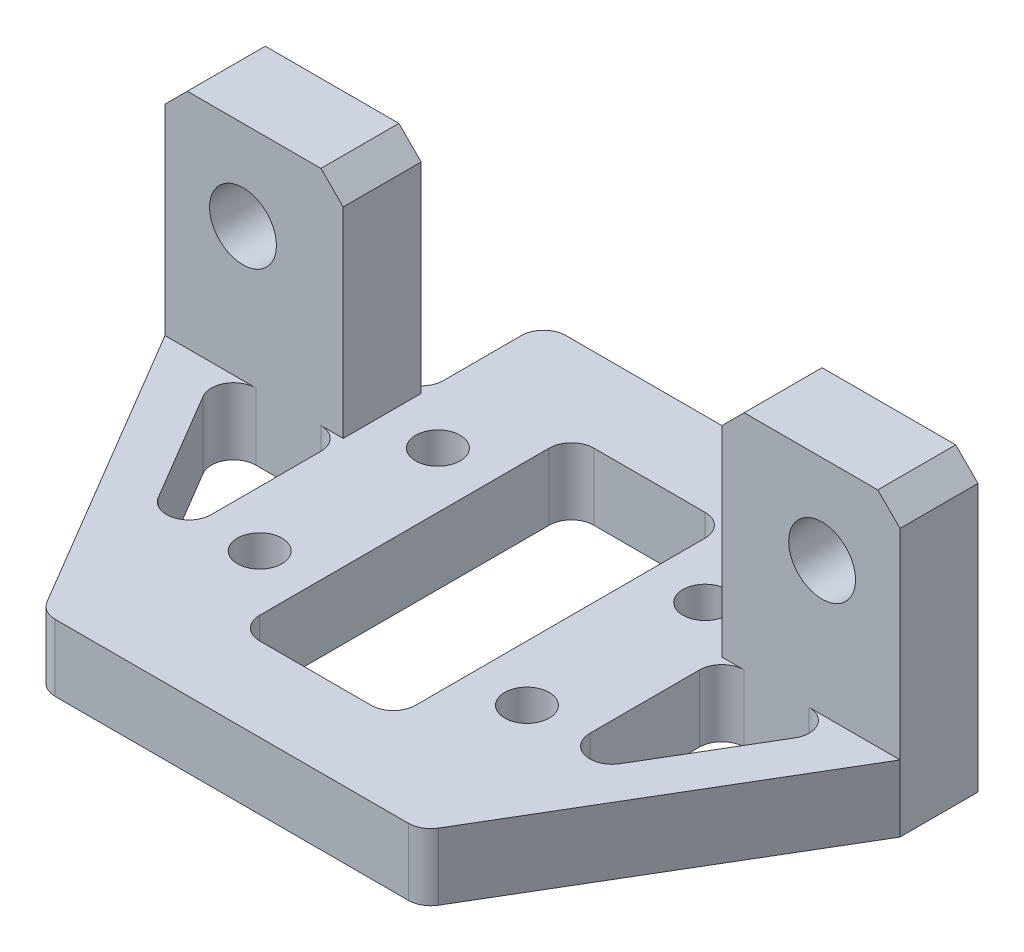
SolidWorks part; units mm, degrees
material "6061-T6 (SS)"
ref_plane "前视基准面" through (0, 0, 0) normal (0, 0, 1) x (1, 0, 0)
ref_plane "上视基准面" through (0, 0, 0) normal (0, 1, 0) x (1, 0, 0)
ref_plane "右视基准面" through (0, 0, 0) normal (1, 0, 0) x (0, 0, -1)
sketch "草图1" plane through (0, 0, 0) normal (0, 1, 0) x (1, 0, 0)
  line L1 (-8.5, 11.25) -> (8.5, 11.25)
  line L2 (-8.5, 11.25) -> (-8.5, -11.25)
  line L3 (-8.5, -11.25) -> (8.5, -11.25)
  line L4 (8.5, 11.25) -> (8.5, -11.25)
  line L5 (-8.5, 11.25) -> (8.5, -11.25) construction
  line L6 (-8.5, -11.25) -> (8.5, 11.25) construction
  point P0 (0, 0)
  dimension "D1" = 17
  dimension "D2" = 22.5
extrude "凸台-拉伸1" add sketch "草图1" along normal blind 3
sketch "草图2" plane through (0, 0, -11.25) normal (0, 0, 1) x (1, 0, 0)
  line L0 (0, 17.6156) -> (0, -12.1631) construction
  line L1 (-16.4166, 0) -> (16.265, 0) construction
  line L3 (-16.5, 13) -> (16.5, 13)
  line L4 (-16.5, 13) -> (-16.5, 0)
  line L5 (-16.5, 0) -> (16.5, 0)
  line L6 (16.5, 13) -> (16.5, 0)
  line L7 (-16.5, 13) -> (16.5, 0) construction
  line L8 (-16.5, 0) -> (16.5, 13) construction
  circle A0 centre (-13, 9) radius 1.5
  circle A1 centre (13, 9) radius 1.5
  point P5 (0, 6.5)
  dimension "D3" = 3
  dimension "D1" = 13
  dimension "D2" = 33
  dimension "D4" = 9
  dimension "D5" = 26
extrude "凸台-拉伸2" add sketch "草图2" along normal blind 3.5 from offset 5.5
sketch "草图3" plane through (0, 0, 0) normal (0, -1, 0) x (1, 0, 0)
  line L0 (0, -28.0972) -> (0, 24.9412) construction
  line L1 (23.039, 0) -> (-25.0172, 0) construction
  circle A0 centre (6, -4) radius 1
  circle A1 centre (-6, -4) radius 1
  circle A2 centre (-6, 4) radius 1
  circle A3 centre (6, 4) radius 1
  dimension "D1" = 2
  dimension "D2" = 12
  dimension "D3" = 8
extrude "切除-拉伸1" cut sketch "草图3" against normal through all
sketch "草图4" plane through (0, 13, 0) normal (0, 1, 0) x (1, 0, 0)
  line L0 (0, 14.4806) -> (0, -10.1377) construction
  line L6 (-6, 4) -> (6, 4) construction
  line L7 (16.5, 2.25) -> (-16.5, 2.25) construction
  line L13 (-8.5, 5.75) -> (8.5, 5.75)
  line L14 (-8.5, 5.75) -> (-8.5, 2.25)
  line L15 (-8.5, 2.25) -> (8.5, 2.25)
  line L16 (8.5, 5.75) -> (8.5, 2.25)
  line L17 (-8.5, 5.75) -> (8.5, 2.25) construction
  line L18 (-8.5, 2.25) -> (8.5, 5.75) construction
  line L21 (-8.5, 2.25) -> (-8.5, -11.25) construction
  point P1 (0, 4)
extrude "切除-拉伸2" cut sketch "草图4" against normal up to surface (10 mm away) up to face at (6, 3, 5)
sketch "草图5" plane through (0, 3, 0) normal (0, 1, 0) x (1, 0, 0)
  line L1 (-3.5, 7.5) -> (3.5, 7.5)
  line L2 (-3.5, 7.5) -> (-3.5, -7.5)
  line L3 (-3.5, -7.5) -> (3.5, -7.5)
  line L4 (3.5, 7.5) -> (3.5, -7.5)
  line L5 (-3.5, 7.5) -> (3.5, -7.5) construction
  line L6 (-3.5, -7.5) -> (3.5, 7.5) construction
  point P0 (0, 0)
  dimension "D1" = 7
  dimension "D2" = 15
extrude "切除-拉伸3" cut sketch "草图5" against normal through all
sketch "草图6" plane through (0, 0, 0) normal (0, -1, 0) x (1, 0, 0)
  line L0 (-16.5, -2.25) -> (-8.5, 11.25)
  line L1 (-14.1752, -2.25) -> (-8.5, 7.3269)
  line L2 (-16.5, -2.25) -> (-8.5, -2.25) construction
  line L3 (-16.5, -2.25) -> (-14.1752, -2.25)
  line L4 (-8.5, -2.25) -> (-8.5, 11.25) construction
  line L5 (-8.5, 7.3269) -> (-8.5, 11.25)
  line L6 (0, -17.4214) -> (0, 13.5809) construction
  line L7 (-14.7794, -3.2696) -> (-6.7794, 10.2304) construction
  line L8 (14.1752, -2.25) -> (8.5, 7.3269)
  line L9 (16.5, -2.25) -> (14.1752, -2.25)
  line L10 (16.5, -2.25) -> (8.5, 11.25)
  line L11 (8.5, 7.3269) -> (8.5, 11.25)
  dimension "D1" = 2
extrude "凸台-拉伸3" add sketch "草图6" against normal up to surface (3 mm away) up to face at (0, 3, 0)
fillet "圆角1" radius 1 10 edges at (8.5, 1.5, -2.25) (-8.5, 1.5, -2.25) (8.5, 1.5, 7.3269) (14.1752, 1.5, -2.25) (-8.5, 1.5, 7.3269) (-14.1752, 1.5, -2.25) (-3.5, 1.5, 7.5) (-3.5, 1.5, -7.5) (3.5, 1.5, -7.5) (3.5, 1.5, 7.5)
fillet "圆角2" radius 1 6 edges at (8.5, 1.5, -11.25) (-8.5, 1.5, -11.25) (8.5, 1.5, 11.25) (-8.5, 1.5, 11.25) (8.5, 1.5, -5.75) (-8.5, 1.5, -5.75)
chamfer "倒角2" distance 1 angle 45 4 edges at (16.5, 13, -4) (8.5, 13, -4) (-8.5, 13, -4) (-16.5, 13, -4)
